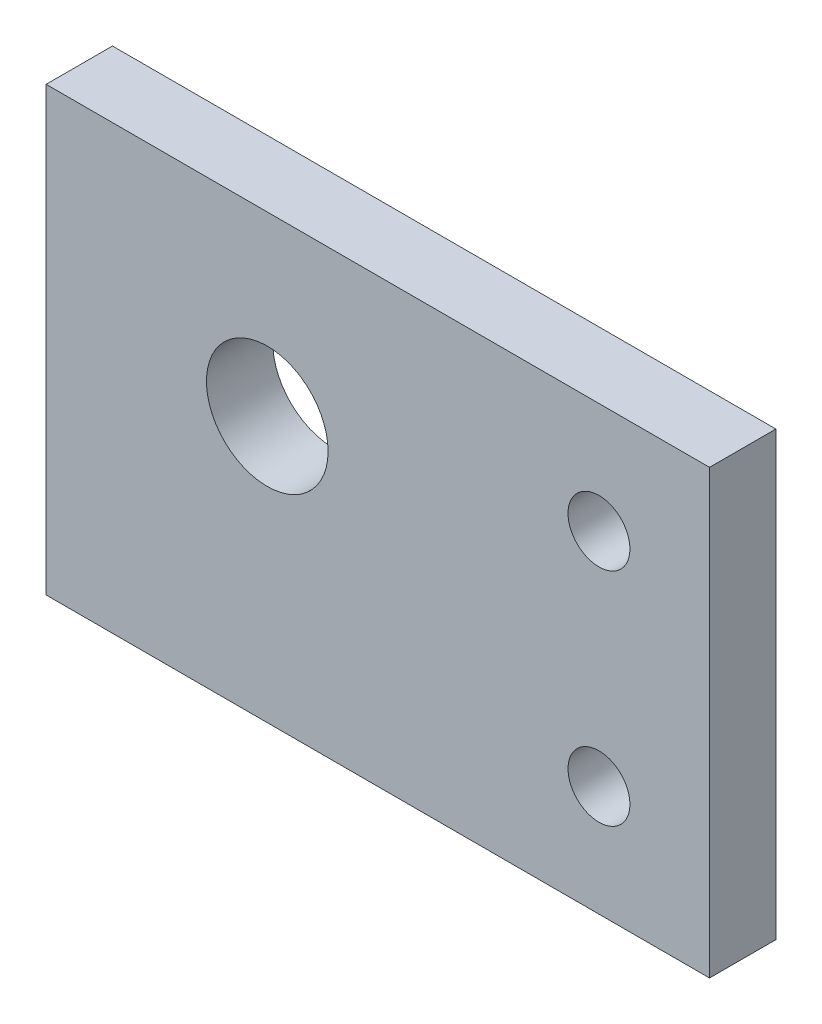
SolidWorks part; units mm, degrees
ref_plane "Front Plane" through (0, 0, 0) normal (0, 0, 1) x (1, 0, 0)
ref_plane "Top Plane" through (0, 0, 0) normal (0, 1, 0) x (1, 0, 0)
ref_plane "Right Plane" through (0, 0, 0) normal (1, 0, 0) x (0, 0, -1)
sketch "Sketch1" plane through (0, 0, 0) normal (0, 0, 1) x (1, 0, 0)
  line L1 (-24.3548, 15.9677) -> (5.6452, 15.9677)
  line L2 (-24.3548, 15.9677) -> (-24.3548, -4.0323)
  line L3 (-24.3548, -4.0323) -> (5.6452, -4.0323)
  line L4 (5.6452, 15.9677) -> (5.6452, -4.0323)
  circle A0 centre (-14.3548, 7.9677) radius 2.75
  circle A1 centre (0.6452, 10.9677) radius 1.4
  circle A2 centre (0.6452, 0.9677) radius 1.4
  dimension "D3" = 5.5
  dimension "D4" = 10
  dimension "D5" = 8
  dimension "D6" = 2.8
  dimension "D7" = 2.8
  dimension "D8" = 5
  dimension "D9" = 5
  dimension "D10" = 10
  dimension "D11" = 5
  dimension "D1" = 20
  dimension "D2" = 30
extrude "Boss-Extrude1" add sketch "Sketch1" along normal blind 3
